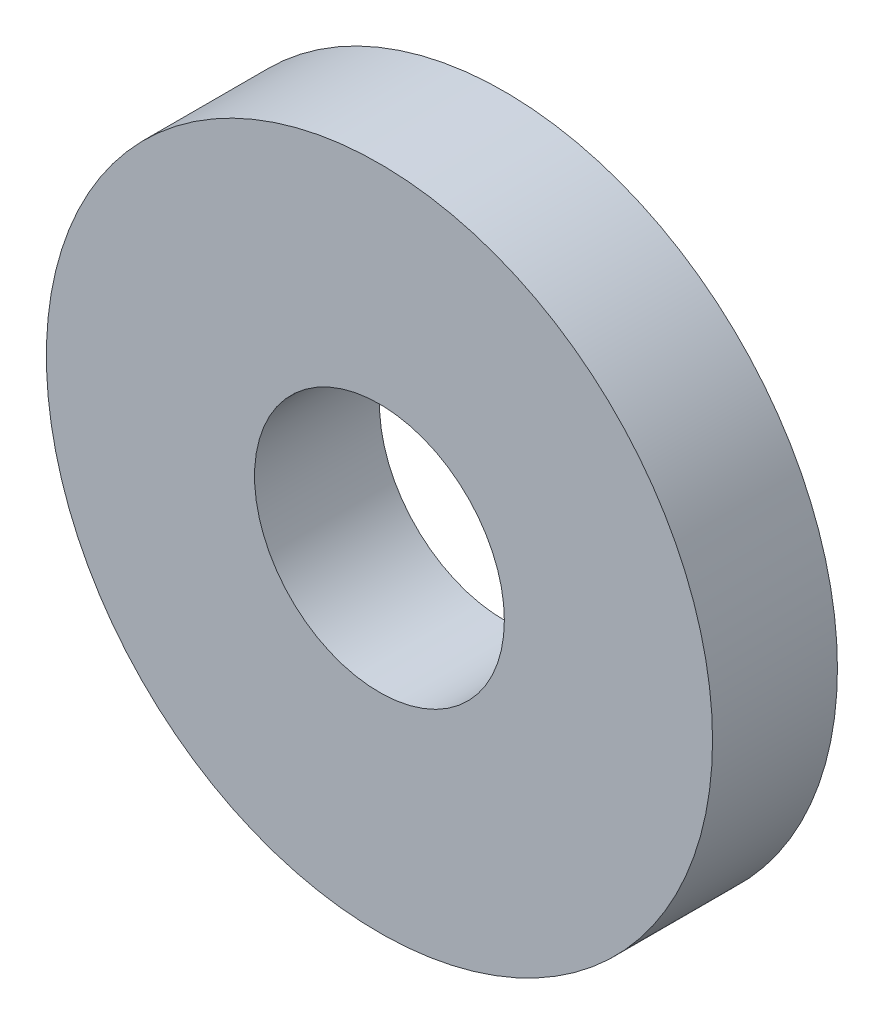
SolidWorks part; units mm, degrees
ref_plane "前视基准面" through (0, 0, 0) normal (0, 0, 1) x (1, 0, 0)
ref_plane "上视基准面" through (0, 0, 0) normal (0, 1, 0) x (1, 0, 0)
ref_plane "右视基准面" through (0, 0, 0) normal (1, 0, 0) x (0, 0, -1)
sketch "Sketch1" plane through (0, 0, 0) normal (0, 0, 1) x (1, 0, 0)
  circle A0 centre (0, 0) radius 32
  circle A1 centre (0, 0) radius 12
  dimension "D1" = 24
  dimension "D2" = 64
extrude "Boss-Extrude1" add sketch "Sketch1" along normal blind 12
